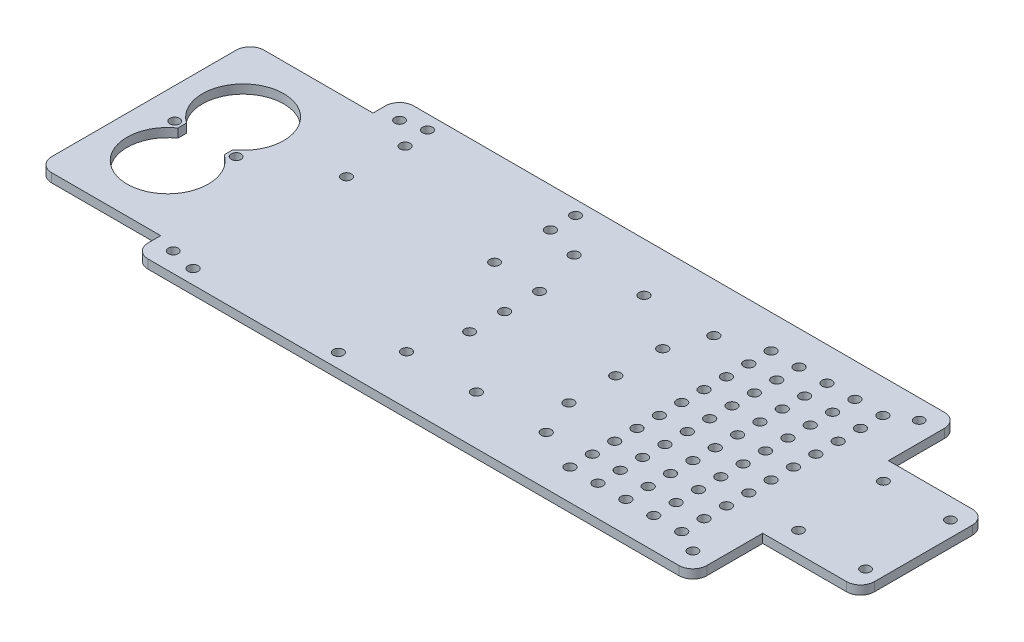
SolidWorks part; units mm, degrees
ref_plane "Front Plane" through (0, 0, 0) normal (0, 0, 1) x (1, 0, 0)
ref_plane "Top Plane" through (0, 0, 0) normal (0, 1, 0) x (1, 0, 0)
ref_plane "Right Plane" through (0, 0, 0) normal (1, 0, 0) x (0, 0, -1)
sketch "Sketch1" plane through (0, 0, 0) normal (0, 1, 0) x (1, 0, 0)
  line L1 (-93.9861, 51.2286) -> (106.0139, 51.2286)
  line L2 (-93.9861, 51.2286) -> (-93.9861, -43.7714)
  line L3 (-93.9861, -43.7714) -> (106.0139, -43.7714)
  line L4 (106.0139, 51.2286) -> (106.0139, -43.7714)
  dimension "D1" = 200
  dimension "D2" = 95
extrude "Boss-Extrude1" add sketch "Sketch1" along normal blind 3.175
sketch "Sketch3" plane through (0, 3.175, 0) normal (0, 1, 0) x (1, 0, 0)
  line L0 (-93.9861, 51.2286) -> (-93.9861, -43.7714) construction
  line L1 (106.0139, 51.2286) -> (-93.9861, 51.2286) construction
  line L4 (-93.9861, -43.7714) -> (106.0139, -43.7714) construction
  line L5 (106.0139, -43.7714) -> (106.0139, 51.2286) construction
  circle A0 centre (-86.9861, -36.7714) radius 1.75
  circle A1 centre (-86.9861, 44.2286) radius 1.75
  circle A2 centre (99.0139, 44.2286) radius 1.75
  circle A3 centre (99.0139, -36.7714) radius 1.75
  dimension "D1" = 3.5
  dimension "D2" = 7
  dimension "D3" = 7
  dimension "D4" = 7
  dimension "D5" = 7
  dimension "D6" = 186
  dimension "D7" = 81
extrude "Cut-Extrude2" cut sketch "Sketch3" against normal through all
sketch "Sketch4" plane through (-93.9861, 0, 0) normal (-1, 0, 0) x (0, 0, 1)
  line L0 (-3.7286, 0) -> (-3.7286, 3.175) construction
  line L1 (-51.2286, 0) -> (43.7714, 0) construction
  line L2 (-51.2286, 3.175) -> (43.7714, 3.175) construction
  line L4 (-41.7286, 0) -> (34.2714, 0)
  line L5 (-41.7286, 0) -> (-41.7286, 3.175)
  line L6 (-41.7286, 3.175) -> (34.2714, 3.175)
  line L7 (34.2714, 0) -> (34.2714, 3.175)
  dimension "D1" = 76
extrude "Boss-Extrude2" add sketch "Sketch4" along normal blind 44
sketch "Sketch5" plane through (0, 3.175, 0) normal (0, 1, 0) x (1, 0, 0)
  line L0 (-137.9861, 3.7286) -> (-93.9861, 3.7286) construction
  line L1 (-137.9861, -34.2714) -> (-137.9861, 41.7286) construction
  line L2 (-115.9861, -9.7714) -> (-115.9861, 17.2286) construction
  line L3 (-124.2861, 2.1791) -> (-124.2861, 5.2782)
  line L4 (-107.6861, 2.1791) -> (-107.6861, 5.2782)
  line L5 (-137.9861, -34.2714) -> (-93.9861, -34.2714) construction
  arc A0 (-124.2861, 2.1791) -> (-107.6861, 2.1791) centre (-115.9861, -9.7714) ccw
  arc A1 (-107.6861, 5.2782) -> (-124.2861, 5.2782) centre (-115.9861, 17.2286) ccw
  circle A2 centre (-126.9861, 3.7286) radius 1.75
  circle A3 centre (-104.9861, 3.7286) radius 1.75
  dimension "D2" = 29.1
  dimension "D4" = 3.5
  dimension "D1" = 27
  dimension "D3" = 16.6
  dimension "D5" = 22
extrude "Cut-Extrude3" cut sketch "Sketch5" against normal through all
sketch "Sketch7" plane through (106.0139, 0, 0) normal (1, 0, 0) x (0, 0, -1)
  line L0 (3.7286, 0) -> (3.7286, 3.175) construction
  line L1 (-43.7714, 0) -> (51.2286, 0) construction
  line L2 (-43.7714, 3.175) -> (51.2286, 3.175) construction
  line L4 (-18.7714, 0) -> (26.2286, 0)
  line L5 (-18.7714, 0) -> (-18.7714, 3.175)
  line L6 (-18.7714, 3.175) -> (26.2286, 3.175)
  line L7 (26.2286, 0) -> (26.2286, 3.175)
  dimension "D1" = 45
extrude "Boss-Extrude3" add sketch "Sketch7" along normal blind 35
sketch "Sketch8" plane through (0, 3.175, 0) normal (0, 1, 0) x (1, 0, 0)
  line L0 (123.5139, -18.7714) -> (123.5139, 26.2286) construction
  line L1 (106.0139, 3.7286) -> (141.0139, 3.7286) construction
  line L2 (141.0139, 26.2286) -> (141.0139, -18.7714) construction
  line L3 (141.0139, -18.7714) -> (106.0139, -18.7714) construction
  line L4 (141.0139, 26.2286) -> (106.0139, 26.2286) construction
  circle A0 centre (111.5139, -11.4714) radius 1.75
  circle A1 centre (111.5139, 18.9286) radius 1.75
  circle A2 centre (135.5139, -11.4714) radius 1.75
  circle A3 centre (135.5139, 18.9286) radius 1.75
  dimension "D1" = 3.5
  dimension "D2" = 24
  dimension "D3" = 30.4
extrude "Cut-Extrude4" cut sketch "Sketch8" against normal through all
fillet "Fillet1" radius 5 8 edges at (106.0139, 1.5875, -51.2286) (141.0139, 1.5875, -26.2286) (141.0139, 1.5875, 18.7714) (106.0139, 1.5875, 43.7714) (-93.9861, 1.5875, -51.2286) (-93.9861, 1.5875, 43.7714) (-137.9861, 1.5875, -41.7286) (-137.9861, 1.5875, 34.2714)
sketch "Sketch9" plane through (0, 3.175, 0) normal (0, 1, 0) x (1, 0, 0)
  line L0 (-78.9861, 46.2286) -> (-25.9861, 46.2286) construction
  line L1 (-25.9861, 46.2286) -> (-25.9861, 17.2286) construction
  line L2 (-25.9861, 17.2286) -> (-78.9861, 17.2286) construction
  line L3 (-78.9861, 17.2286) -> (-78.9861, 46.2286) construction
  line L4 (101.0139, 51.2286) -> (-88.9861, 51.2286) construction
  circle A0 centre (-78.9861, 46.2286) radius 1.775
  circle A1 centre (-25.9861, 46.2286) radius 1.775
  circle A2 centre (-25.9861, 17.2286) radius 1.775
  circle A3 centre (-78.9861, 17.2286) radius 1.775
  circle A4 centre (-86.9861, 44.2286) radius 1.75 construction
  dimension "D1" = 3.55
  dimension "D4" = 8
  dimension "D2" = 53
  dimension "D3" = 29
  dimension "D5" = 5
extrude "Cut-Extrude5" cut sketch "Sketch9" against normal through all
sketch "Sketch10" plane through (0, 3.175, 0) normal (0, 1, 0) x (1, 0, 0)
  line L0 (-137.9861, 3.7286) -> (141.0139, 3.7286) construction
  line L1 (141.0139, 21.2286) -> (141.0139, -13.7714) construction
  line L2 (-137.9861, -29.2714) -> (-137.9861, 36.7286) construction
  line L3 (11.0139, -26.2714) -> (11.0139, 33.7286) construction
  circle A0 centre (-13.9861, 33.7286) radius 1.8
  circle A1 centre (11.0139, 33.7286) radius 1.8
  circle A2 centre (36.0139, 33.7286) radius 1.8
  circle A3 centre (-13.9861, -26.2714) radius 1.8
  circle A4 centre (11.0139, -26.2714) radius 1.8
  circle A5 centre (36.0139, -26.2714) radius 1.8
  circle A6 centre (-8.8861, 3.7286) radius 1.8
  circle A7 centre (30.9139, 3.7286) radius 1.8
  circle A8 centre (-8.8861, 16.2286) radius 1.775
  circle A9 centre (-8.8861, -8.7714) radius 1.775
  circle A10 centre (30.9139, -13.0714) radius 1.8
  circle A11 centre (30.9139, 20.5286) radius 1.8
  dimension "D1" = 3.6
  dimension "D5" = 3.6
  dimension "D7" = 3.55
  dimension "D10" = 3.6
  dimension "D2" = 25
  dimension "D3" = 25
  dimension "D4" = 60
  dimension "D6" = 39.8
  dimension "D8" = 25
  dimension "D9" = 33.6
  dimension "D11" = 130
extrude "Cut-Extrude6" cut sketch "Sketch10" against normal through all
sketch "Sketch11" plane through (0, 3.175, 0) normal (0, 1, 0) x (1, 0, 0)
  line L0 (-77.9861, -38.6714) -> (-77.9861, 37.2286) construction
  line L1 (-77.9861, 37.2286) -> (-25.9861, 37.2286) construction
  line L2 (-25.9861, 37.2286) -> (-25.9861, -38.6714) construction
  line L3 (-25.9861, -38.6714) -> (-77.9861, -38.6714) construction
  line L4 (101.0139, 51.2286) -> (-88.9861, 51.2286) construction
  line L5 (-137.9861, -29.2714) -> (-137.9861, 36.7286) construction
  circle A0 centre (-77.9861, 37.2286) radius 1.8
  circle A1 centre (-25.9861, 37.2286) radius 1.8
  circle A2 centre (-77.9861, -38.6714) radius 1.8
  circle A3 centre (-25.9861, -38.6714) radius 1.8
  circle A4 centre (-25.9861, 46.2286) radius 1.775 construction
  dimension "D1" = 3.6
  dimension "D2" = 75.9
  dimension "D3" = 52
  dimension "D4" = 14
  dimension "D5" = 60
extrude "Cut-Extrude7" cut sketch "Sketch11" against normal through all
sketch "Sketch12" plane through (0, 3.175, 0) normal (0, 1, 0) x (1, 0, 0)
  line L0 (141.0139, 21.2286) -> (141.0139, -13.7714) construction
  line L1 (101.0139, 51.2286) -> (-88.9861, 51.2286) construction
  circle A0 centre (51.0139, 39.2286) radius 1.8
  circle A1 centre (51.0139, 31.2286) radius 1.8
  circle A2 centre (51.0139, 23.2286) radius 1.8
  circle A3 centre (51.0139, 15.2286) radius 1.8
  circle A4 centre (51.0139, 7.2286) radius 1.8
  circle A5 centre (51.0139, -0.7714) radius 1.8
  circle A6 centre (51.0139, -8.7714) radius 1.8
  circle A7 centre (51.0139, -16.7714) radius 1.8
  circle A8 centre (51.0139, -24.7714) radius 1.8
  circle A9 centre (51.0139, -32.7714) radius 1.8
  circle A10 centre (61.0139, 31.2286) radius 1.8
  circle A11 centre (61.0139, 23.2286) radius 1.8
  circle A12 centre (61.0139, 15.2286) radius 1.8
  circle A13 centre (61.0139, 7.2286) radius 1.8
  circle A14 centre (61.0139, -0.7714) radius 1.8
  circle A15 centre (61.0139, -8.7714) radius 1.8
  circle A16 centre (61.0139, -16.7714) radius 1.8
  circle A17 centre (61.0139, -24.7714) radius 1.8
  circle A18 centre (61.0139, -32.7714) radius 1.8
  circle A19 centre (71.0139, 31.2286) radius 1.8
  circle A20 centre (71.0139, 23.2286) radius 1.8
  circle A21 centre (71.0139, 15.2286) radius 1.8
  circle A22 centre (71.0139, 7.2286) radius 1.8
  circle A23 centre (71.0139, -0.7714) radius 1.8
  circle A24 centre (71.0139, -8.7714) radius 1.8
  circle A25 centre (71.0139, -16.7714) radius 1.8
  circle A26 centre (71.0139, -24.7714) radius 1.8
  circle A27 centre (71.0139, -32.7714) radius 1.8
  circle A28 centre (81.0139, 31.2286) radius 1.8
  circle A29 centre (81.0139, 23.2286) radius 1.8
  circle A30 centre (81.0139, 15.2286) radius 1.8
  circle A31 centre (81.0139, 7.2286) radius 1.8
  circle A32 centre (81.0139, -0.7714) radius 1.8
  circle A33 centre (81.0139, -8.7714) radius 1.8
  circle A34 centre (81.0139, -16.7714) radius 1.8
  circle A35 centre (81.0139, -24.7714) radius 1.8
  circle A36 centre (81.0139, -32.7714) radius 1.8
  circle A37 centre (91.0139, 31.2286) radius 1.8
  circle A38 centre (91.0139, 23.2286) radius 1.8
  circle A39 centre (91.0139, 15.2286) radius 1.8
  circle A40 centre (91.0139, 7.2286) radius 1.8
  circle A41 centre (91.0139, -0.7714) radius 1.8
  circle A42 centre (91.0139, -8.7714) radius 1.8
  circle A43 centre (91.0139, -16.7714) radius 1.8
  circle A44 centre (91.0139, -24.7714) radius 1.8
  circle A45 centre (91.0139, -32.7714) radius 1.8
  circle A46 centre (61.0139, 39.2286) radius 1.8
  circle A47 centre (71.0139, 39.2286) radius 1.8
  circle A48 centre (81.0139, 39.2286) radius 1.8
  circle A49 centre (91.0139, 39.2286) radius 1.8
  dimension "D1" = 3.6
  dimension "D4" = 50
  dimension "D5" = 12
  dimension "D2" = 10
  dimension "D3" = 5
extrude "Cut-Extrude8" cut sketch "Sketch12" against normal through all
